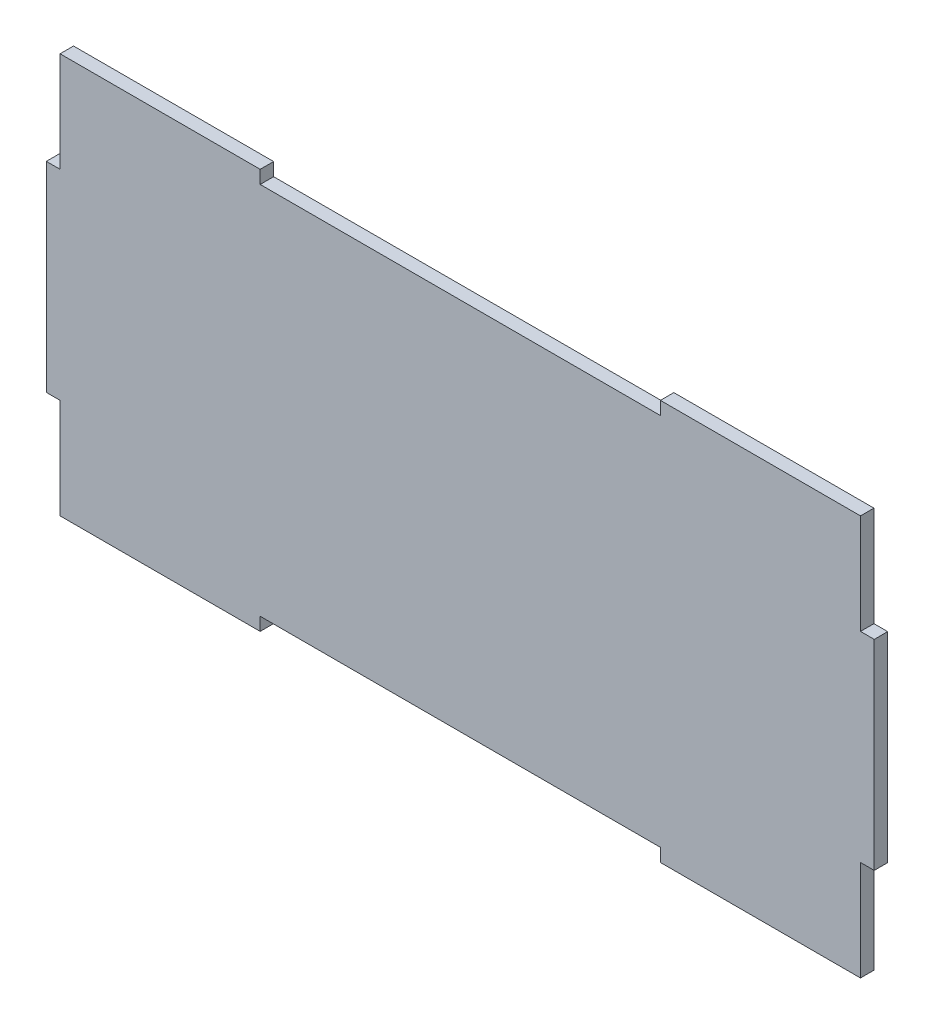
SolidWorks part; units mm, degrees
ref_plane "Front Plane" through (0, 0, 0) normal (0, 0, 1) x (1, 0, 0)
ref_plane "Top Plane" through (0, 0, 0) normal (0, 1, 0) x (1, 0, 0)
ref_plane "Right Plane" through (0, 0, 0) normal (1, 0, 0) x (0, 0, -1)
sketch "Sketch1" plane through (0, 0, 0) normal (0, 0, 1) x (1, 0, 0)
  line L1 (-100, 50) -> (100, 50)
  line L2 (-100, 50) -> (-100, -50)
  line L3 (-100, -50) -> (100, -50)
  line L4 (100, 50) -> (100, -50)
  line L5 (-100, 50) -> (100, -50) construction
  line L6 (-100, -50) -> (100, 50) construction
  point P0 (0, 0)
  dimension "D1" = 100
  dimension "D2" = 200
extrude "Boss-Extrude1" add sketch "Sketch1" along normal blind 3.36
sketch "Sketch2" [suppressed] plane through (0, 0, 3.36) normal (0, 0, 1) x (1, 0, 0)
  line L0 (50, 50) -> (-50, 50) construction
  line L1 (-25, 50) -> (25, 50)
  line L2 (-25, 50) -> (-25, 53.36)
  line L3 (-25, 53.36) -> (25, 53.36)
  line L4 (25, 50) -> (25, 53.36)
  line L5 (0, 0) -> (0, 53.36) construction
  line L6 (0, 0) -> (50, 0) construction
  line L7 (50, -50) -> (50, 50) construction
  dimension "D1" = 3.36
  dimension "D2" = 50
sketch "Sketch8" plane through (0, 0, 0) normal (0, 0, -1) x (-1, 0, 0)
  line L0 (0, 0) -> (0, 50) construction
  line L1 (-100, 50) -> (100, 50) construction
  line L2 (0, 0) -> (100, 0) construction
  line L3 (100, 50) -> (100, -50) construction
  line L5 (-50, 50) -> (50, 50)
  line L6 (-50, 50) -> (-50, 53.44)
  line L7 (-50, 53.44) -> (50, 53.44)
  line L8 (50, 50) -> (50, 53.44)
  dimension "D2" = 3.44
  dimension "D1" = 100
extrude "Boss-Extrude4" [suppressed] add sketch "Sketch8" against normal blind 3.36
mirror "Mirror4" [suppressed] about plane through (0, 0, 0) normal (0, 1, 0)
sketch "Sketch9" plane through (0, 0, 0) normal (0, 0, -1) x (-1, 0, 0)
  line L0 (0, 0) -> (100, 0) construction
  line L1 (100, 50) -> (100, -50) construction
  line L3 (100, 25) -> (103.44, 25)
  line L4 (100, 25) -> (100, -25)
  line L5 (100, -25) -> (103.44, -25)
  line L6 (103.44, 25) -> (103.44, -25)
  dimension "D1" = 50
  dimension "D2" = 3.44
extrude "Boss-Extrude5" add sketch "Sketch9" against normal blind 3.36
mirror "Mirror5" about plane through (0, 0, 0) normal (1, 0, 0) of "Boss-Extrude5"
sketch "Sketch10" plane through (0, 0, 3.36) normal (0, 0, 1) x (1, 0, 0)
  line L0 (0, 0) -> (0, 50) construction
  line L1 (100, 50) -> (-100, 50) construction
  line L3 (-50, 50) -> (50, 50)
  line L4 (-50, 50) -> (-50, 46.72)
  line L5 (-50, 46.72) -> (50, 46.72)
  line L6 (50, 50) -> (50, 46.72)
  dimension "D1" = 3.28
  dimension "D2" = 100
extrude "Cut-Extrude1" cut sketch "Sketch10" against normal blind 3.36
mirror "Mirror6" about plane through (0, 0, 0) normal (0, 1, 0) of "Cut-Extrude1"
sketch "Sketch11" plane through (0, 0, 3.36) normal (0, 0, 1) x (1, 0, 0)
  line L0 (0, 0) -> (100, 0) construction
  line L1 (100, -50) -> (100, -25) construction
  line L3 (100, 25) -> (96.72, 25)
  line L4 (100, 25) -> (100, -25)
  line L5 (100, -25) -> (96.72, -25)
  line L6 (96.72, 25) -> (96.72, -25)
  dimension "D2" = 50
  dimension "D1" = 3.28
extrude "Cut-Extrude2" [suppressed] cut sketch "Sketch11" against normal through all
mirror "Mirror7" [suppressed] about plane through (0, 0, 0) normal (1, 0, 0)
sketch "Sketch12" plane through (0, 0, 3.36) normal (0, 0, 1) x (1, 0, 0)
  line L0 (-100, -25) -> (-100, -50) construction
  line L1 (-100, -50) -> (-50, -50) construction
  line L2 (-85, -35) -> (-85, 13.3) construction
  line L3 (-32.6, -2) -> (-32.6, -29.9) construction
  circle A0 centre (-85, -35) radius 1.6
  circle A1 centre (-83.4, 13.3) radius 1.6
  circle A2 centre (-32.6, -29.9) radius 1.6
  circle A3 centre (-32.6, -2) radius 1.6
  dimension "D1" = 3.2
  dimension "D2" = 15
  dimension "D3" = 15
  dimension "D4" = 3.2
  dimension "D5" = 48.3
  dimension "D6" = 3.2
  dimension "D8" = 3.2
  dimension "D9" = 50.8
  dimension "D10" = 27.9
extrude "Cut-Extrude3" [suppressed] cut sketch "Sketch12" against normal blind 10
sketch "Sketch13" plane through (0, 0, 3.36) normal (0, 0, 1) x (1, 0, 0)
  line L0 (75.9457, -17.2496) -> (33.6649, -17.2496) construction
  line L1 (100, -50) -> (100, -25) construction
  line L2 (50, -50) -> (100, -50) construction
  circle A0 centre (75.9457, -17.2496) radius 2
  circle A1 centre (33.6649, 3.9716) radius 2
  circle A2 centre (33.6649, -38.4708) radius 2
  dimension "D1" = 4
  dimension "D2" = 42.4424
  dimension "D3" = 42.2808
  dimension "D4" = 24.0543
  dimension "D5" = 32.7504
extrude "Cut-Extrude4" [suppressed] cut sketch "Sketch13" against normal blind 10
equation "\"Sheet Thickness\"= 3.36mm"
equation "\"Height\"= 100mm"
equation "\"Length\"= 200mm"
equation "\"Width\"= 100mm"
equation "\"D1@Boss-Extrude1\"=\"Sheet Thickness\""
equation "\"D1@Sketch2\"=\"Sheet Thickness\""
equation "\"D2@Sketch2\"=\"Height\"/2"
equation "\"Kerf\"= .08mm"
equation "\"D2@Sketch9\"=\"Sheet Thickness\"+\"Kerf\""
equation "\"D1@Sketch9\"      = \"Height\"/2"
equation "\"D2@Sketch8\"=\"Sheet Thickness\"+\"Kerf\""
equation "\"D1@Sketch10\"=\"Sheet Thickness\"-\"Kerf\""
equation "\"D1@Sketch11\"=\"Sheet Thickness\"-\"Kerf\""
equation "\"D2@Sketch11\"=\"Height\"/2"
equation "\"D2@Sketch1\" = \"Length\""
equation "\"D1@Sketch1\"  = \"Height\""
